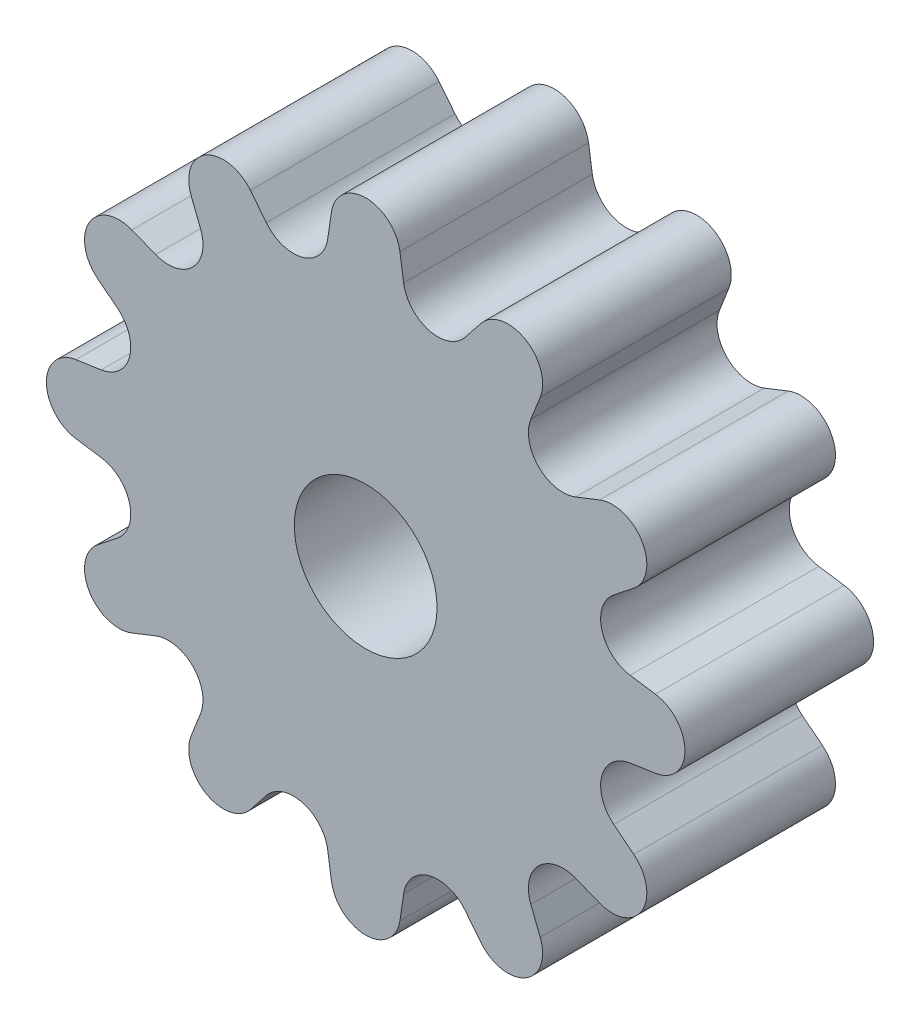
SolidWorks part; units mm, degrees
material "Acrylic (Medium-high impact)"
ref_plane "Front Plane" through (0, 0, 0) normal (0, 0, 1) x (1, 0, 0)
ref_plane "Top Plane" through (0, 0, 0) normal (0, 1, 0) x (1, 0, 0)
ref_plane "Right Plane" through (0, 0, 0) normal (1, 0, 0) x (0, 0, -1)
sketch "Sketch2" plane through (0, 0, 0) normal (0, 0, 1) x (1, 0, 0)
  line L0 (296.7121, 181.0723) -> (298.8322, 188.9846) construction
  line L5 (296.7121, 189.4289) -> (296.7121, 190.4449) construction
  line L7 (300.0946, 188.9409) -> (299.6281, 188.353)
  line L8 (295.7071, 189.5779) -> (295.597, 188.8356)
  line L9 (301.5595, 187.2379) -> (301.8353, 187.9359)
  line L10 (303.5757, 186.1954) -> (302.8778, 185.9196)
  line L12 (303.9929, 183.9882) -> (304.5807, 184.4547)
  line L13 (305.2178, 182.0773) -> (304.4754, 182.1874)
  line L15 (304.4754, 179.9571) -> (305.2178, 180.0673)
  line L16 (304.5807, 177.6898) -> (303.9929, 178.1563)
  line L17 (302.8778, 176.2249) -> (303.5757, 175.9491)
  line L18 (301.8353, 174.2086) -> (301.5595, 174.9066)
  line L20 (299.6281, 173.7915) -> (300.0946, 173.2036)
  line L21 (297.7171, 172.5666) -> (297.8272, 173.3089)
  line L24 (295.597, 173.3089) -> (295.7071, 172.5666)
  line L25 (293.3297, 173.2036) -> (293.7962, 173.7915)
  line L26 (291.8648, 174.9066) -> (291.5889, 174.2086)
  line L27 (289.8485, 175.9491) -> (290.5464, 176.2249)
  line L28 (289.4313, 178.1563) -> (288.8435, 177.6898)
  line L29 (288.2065, 180.0673) -> (288.9488, 179.9571)
  line L30 (288.9488, 182.1874) -> (288.2065, 182.0773)
  line L31 (288.8435, 184.4547) -> (289.4313, 183.9882)
  line L32 (290.5464, 185.9196) -> (289.8485, 186.1954)
  line L34 (291.5889, 187.9359) -> (291.8648, 187.2379)
  line L35 (293.7962, 188.353) -> (293.3297, 188.9409)
  line L43 (297.8272, 188.8356) -> (297.7171, 189.5779)
  line L44 (296.7121, 181.0723) -> (296.7121, 189.4289) construction
  arc A3 (297.8272, 188.8356) -> (298.5693, 188.0033) centre (298.8322, 188.9846) ccw
  arc A4 (297.7171, 189.5779) -> (295.7071, 189.5779) centre (296.7121, 189.4289) ccw
  arc A5 (295.597, 188.8356) -> (294.855, 188.0033) centre (294.592, 188.9846) cw
  arc A6 (299.6281, 188.353) -> (298.5693, 188.0033) centre (298.8322, 188.9846) cw
  arc A7 (301.8353, 187.9359) -> (300.0946, 188.9409) centre (300.8904, 188.3093) ccw
  arc A8 (301.5595, 187.2379) -> (301.786, 186.1461) centre (302.5044, 186.8645) ccw
  arc A9 (302.8778, 185.9196) -> (301.786, 186.1461) centre (302.5044, 186.8645) cw
  arc A10 (304.5807, 184.4547) -> (303.5757, 186.1954) centre (303.9492, 185.2506) ccw
  arc A11 (303.9929, 183.9882) -> (303.6431, 182.9294) centre (304.6245, 183.1924) ccw
  arc A12 (304.4754, 182.1874) -> (303.6431, 182.9294) centre (304.6245, 183.1924) cw
  arc A13 (305.2178, 180.0673) -> (305.2178, 182.0773) centre (305.0687, 181.0723) ccw
  arc A14 (304.4754, 179.9571) -> (303.6431, 179.2151) centre (304.6245, 178.9521) ccw
  arc A15 (303.9929, 178.1563) -> (303.6431, 179.2151) centre (304.6245, 178.9521) cw
  arc A16 (303.5757, 175.9491) -> (304.5807, 177.6898) centre (303.9492, 176.894) ccw
  arc A17 (302.8778, 176.2249) -> (301.786, 175.9984) centre (302.5044, 175.28) ccw
  arc A18 (301.5595, 174.9066) -> (301.786, 175.9984) centre (302.5044, 175.28) cw
  arc A19 (300.0946, 173.2036) -> (301.8353, 174.2086) centre (300.8904, 173.8352) ccw
  arc A20 (299.6281, 173.7915) -> (298.5693, 174.1413) centre (298.8322, 173.1599) ccw
  arc A21 (297.8272, 173.3089) -> (298.5693, 174.1413) centre (298.8322, 173.1599) cw
  arc A22 (295.7071, 172.5666) -> (297.7171, 172.5666) centre (296.7121, 172.7157) ccw
  arc A23 (295.597, 173.3089) -> (294.855, 174.1413) centre (294.592, 173.1599) ccw
  arc A24 (293.7962, 173.7915) -> (294.855, 174.1413) centre (294.592, 173.1599) cw
  arc A25 (291.5889, 174.2086) -> (293.3297, 173.2036) centre (292.5338, 173.8352) ccw
  arc A26 (291.8648, 174.9066) -> (291.6383, 175.9984) centre (290.9199, 175.28) ccw
  arc A27 (290.5464, 176.2249) -> (291.6383, 175.9984) centre (290.9199, 175.28) cw
  arc A28 (288.8435, 177.6898) -> (289.8485, 175.9491) centre (289.4751, 176.894) ccw
  arc A29 (289.4313, 178.1563) -> (289.7811, 179.2151) centre (288.7997, 178.9521) ccw
  arc A30 (288.9488, 179.9571) -> (289.7811, 179.2151) centre (288.7997, 178.9521) cw
  arc A31 (288.2065, 182.0773) -> (288.2065, 180.0673) centre (288.3555, 181.0723) ccw
  arc A32 (288.9488, 182.1874) -> (289.7811, 182.9294) centre (288.7997, 183.1924) ccw
  arc A33 (289.4313, 183.9882) -> (289.7811, 182.9294) centre (288.7997, 183.1924) cw
  arc A34 (289.8485, 186.1954) -> (288.8435, 184.4547) centre (289.4751, 185.2506) ccw
  arc A35 (290.5464, 185.9196) -> (291.6383, 186.1461) centre (290.9199, 186.8645) ccw
  arc A36 (291.8648, 187.2379) -> (291.6383, 186.1461) centre (290.9199, 186.8645) cw
  arc A37 (293.3297, 188.9409) -> (291.5889, 187.9359) centre (292.5338, 188.3093) ccw
  arc A38 (293.7962, 188.353) -> (294.855, 188.0033) centre (294.592, 188.9846) ccw
  point P111 (296.7121, 181.0723)
  dimension "D1" = 12
  dimension "D5" = 1.016
  dimension "D6" = 1.016
  dimension "D2" = 15
  dimension "D3" = 9.3726
  dimension "D4" = 7.1755
extrude "Boss-Extrude1" add sketch "Sketch2" along normal blind 5.5372
sketch "Sketch3" plane through (0, 0, 5.5372) normal (0, 0, 1) x (1, 0, 0)
  circle A0 centre (296.7121, 181.0723) radius 2.0955
  dimension "D1" = 4.191
extrude "Cut-Extrude1" cut sketch "Sketch3" against normal through all
